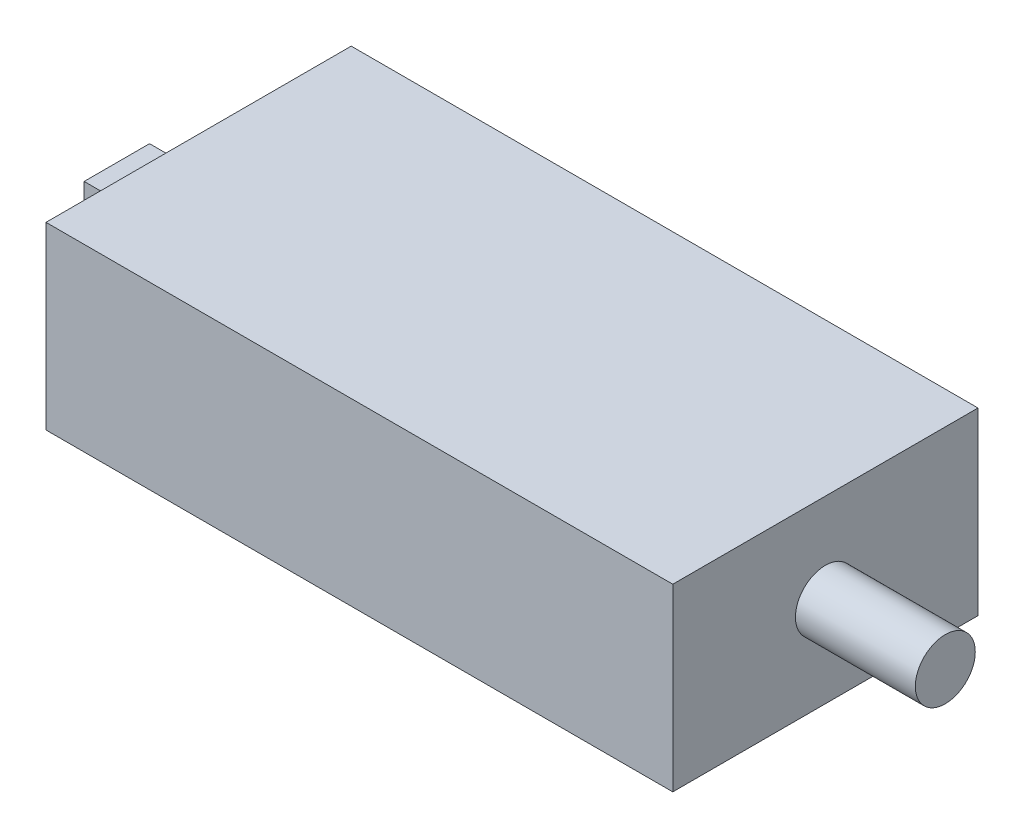
SolidWorks part; units mm, degrees
ref_plane "Płaszczyzna przednia" through (0, 0, 0) normal (0, 0, 1) x (1, 0, 0)
ref_plane "Płaszczyzna górna" through (0, 0, 0) normal (0, 1, 0) x (1, 0, 0)
ref_plane "Płaszczyzna prawa" through (0, 0, 0) normal (1, 0, 0) x (0, 0, -1)
sketch "Szkic1" plane through (0, 0, 0) normal (0, 1, 0) x (1, 0, 0)
  line L1 (0, 0) -> (115, 0)
  line L2 (0, 0) -> (0, 56)
  line L3 (0, 56) -> (115, 56)
  line L4 (115, 0) -> (115, 56)
extrude "Dodanie-wyciągnięcie1" add sketch "Szkic1" along normal blind 33
sketch "Szkic2" plane through (115, 0, 0) normal (1, 0, 0) x (0, 0, -1)
  circle A0 centre (28, 16.5) radius 5.5
extrude "Dodanie-wyciągnięcie2" add sketch "Szkic2" along normal blind 22
sketch "Szkic3" plane through (0, 0, 0) normal (-1, 0, 0) x (0, 0, 1)
  line L8 (-34, 16.5) -> (-34, 12)
  line L9 (-34, 12) -> (-22, 12)
  line L10 (-22, 12) -> (-22, 16.5)
  line L11 (-22, 16.5) -> (-22, 21)
  line L12 (-22, 21) -> (-34, 21)
  line L13 (-34, 21) -> (-34, 16.5)
extrude "Dodanie-wyciągnięcie3" add sketch "Szkic3" along normal blind 15
